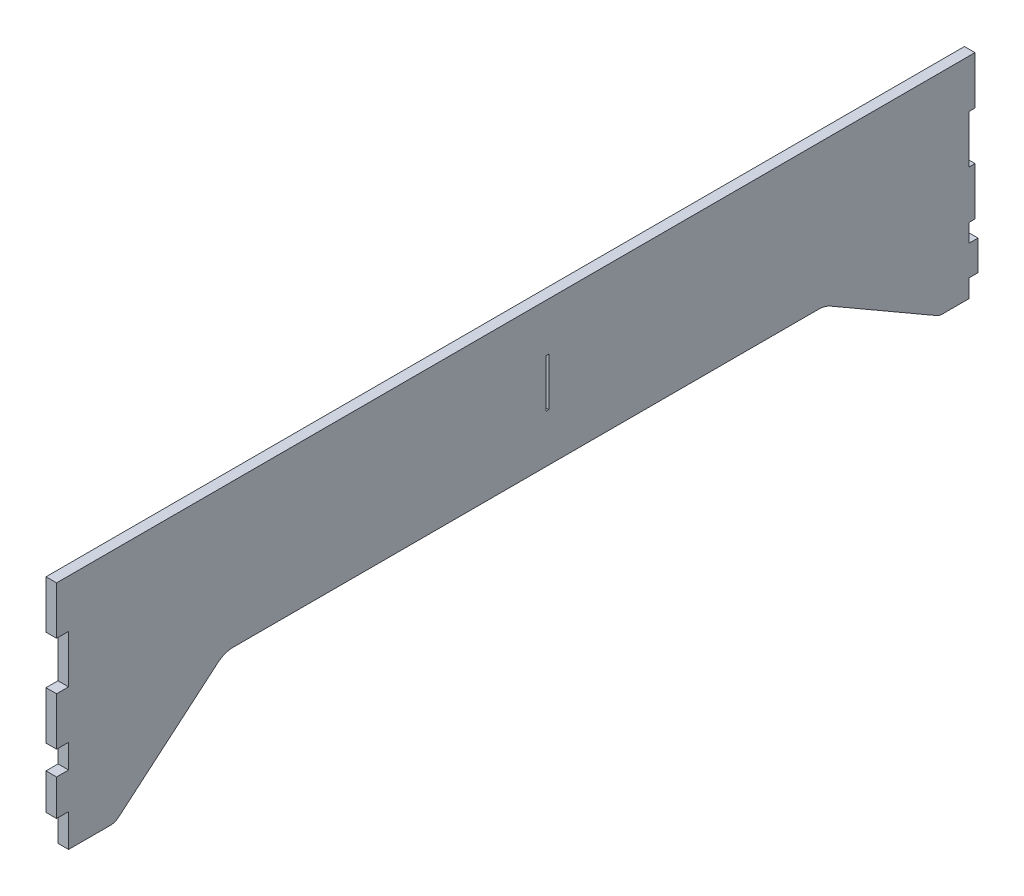
SolidWorks part; units mm, degrees
material "Balsa"
ref_plane "Front Plane" through (0, 0, 0) normal (0, 0, 1) x (1, 0, 0)
ref_plane "Top Plane" through (0, 0, 0) normal (0, 1, 0) x (1, 0, 0)
ref_plane "Right Plane" through (0, 0, 0) normal (1, 0, 0) x (0, 0, -1)
ref_plane "Plane1" through (-94.488, 0, 0) normal (-1, 0, 0) x (0, -1, 0)
sketch "Sketch1" plane through (-94.488, 0, 0) normal (-1, 0, 0) x (0, -1, 0)
  line L0 (111.125, -457.2) -> (85.725, -457.2)
  line L1 (85.725, -457.2) -> (85.725, -455.6125)
  line L2 (85.725, -455.6125) -> (111.125, -455.6125)
  line L3 (111.125, -455.6125) -> (111.125, -457.2)
  line L4 (111.125, -203.2) -> (85.725, -203.2)
  line L5 (85.725, -203.2) -> (85.725, -196.85)
  line L6 (85.725, -196.85) -> (60.325, -196.85)
  line L7 (60.325, -196.85) -> (60.325, -682.625)
  line L8 (60.325, -682.625) -> (85.725, -682.625)
  line L9 (85.725, -682.625) -> (85.725, -679.45)
  line L10 (85.725, -679.45) -> (111.125, -679.45)
  line L11 (111.125, -679.45) -> (111.125, -682.625)
  line L12 (111.125, -682.625) -> (136.525, -682.625)
  line L13 (136.525, -682.625) -> (136.525, -196.85)
  line L14 (136.525, -196.85) -> (111.125, -196.85)
  line L15 (111.125, -196.85) -> (111.125, -203.2)
  line L16 (136.525, -196.85) -> (185.6232, -196.85) construction
  line L17 (185.6232, -196.85) -> (185.6232, -227.7965) construction
  line L18 (184.1182, -229.5729) -> (139.535, -282.1971)
  line L19 (136.525, -203.2) -> (149.225, -203.2)
  line L20 (149.225, -203.2) -> (149.225, -196.85)
  line L21 (168.275, -196.85) -> (168.275, -203.2)
  line L22 (168.275, -203.2) -> (185.6232, -203.2)
  line L23 (185.6232, -203.2) -> (185.6232, -225.4683)
  line L24 (168.275, -196.85) -> (149.225, -196.85)
  line L25 (136.525, -679.45) -> (146.05, -679.45)
  line L26 (146.05, -679.45) -> (146.05, -684.2125)
  line L27 (146.05, -684.2125) -> (161.925, -684.2125)
  line L28 (161.925, -684.2125) -> (161.925, -679.45)
  line L29 (161.925, -679.45) -> (171.45, -679.45)
  line L30 (171.45, -679.45) -> (171.45, -665.4434)
  line L31 (170.5993, -662.2684) -> (138.2265, -606.197)
  circle A0 centre (130.175, -666.75) radius 1.7526 construction
  circle A1 centre (130.175, -615.95) radius 1.7526 construction
  circle A2 centre (130.175, -565.15) radius 1.7526 construction
  circle A3 centre (130.175, -514.35) radius 1.7526 construction
  circle A4 centre (130.175, -463.55) radius 1.7526 construction
  circle A5 centre (130.175, -412.75) radius 1.7526 construction
  circle A6 centre (130.175, -361.95) radius 1.7526 construction
  circle A7 centre (130.175, -311.15) radius 1.7526 construction
  circle A8 centre (130.175, -260.35) radius 1.7526 construction
  circle A9 centre (130.175, -209.55) radius 1.7526 construction
  arc A10 (184.1182, -229.5729) -> (185.6232, -225.4683) centre (179.2732, -225.4683) ccw
  arc A11 (139.535, -282.1971) -> (136.525, -290.4065) centre (149.225, -290.4065) ccw
  arc A12 (136.525, -599.847) -> (138.2265, -606.197) centre (149.225, -599.847) ccw
  arc A13 (171.45, -665.4434) -> (170.5993, -662.2684) centre (165.1, -665.4434) ccw
  point P38 (136.525, -285.75)
  point P58 (136.525, -603.25)
  dimension "D14" = 12.7
  dimension "D15" = 6.35
  dimension "D21" = 12.7
  dimension "D22" = 6.35
  dimension "D1" = 222.25
  dimension "D2" = 485.775
  dimension "D3" = 76.2
  dimension "D4" = 3.175
  dimension "D5" = 6.35
  dimension "D6" = 25.4
  dimension "D7" = 25.4
  dimension "D8" = 1.5875
  dimension "D9" = 49.0982
  dimension "D10" = 82.55
  dimension "D11" = 40.271
  dimension "D12" = 19.05
  dimension "D13" = 12.7
  dimension "D16" = 9.525
  dimension "D17" = 34.925
  dimension "D18" = 15.875
  dimension "D19" = 30
  dimension "D20" = 76.2
  dimension "D23" = 4.7625
extrude "Boss-Extrude1" add sketch "Sketch1" against normal blind 5.588
